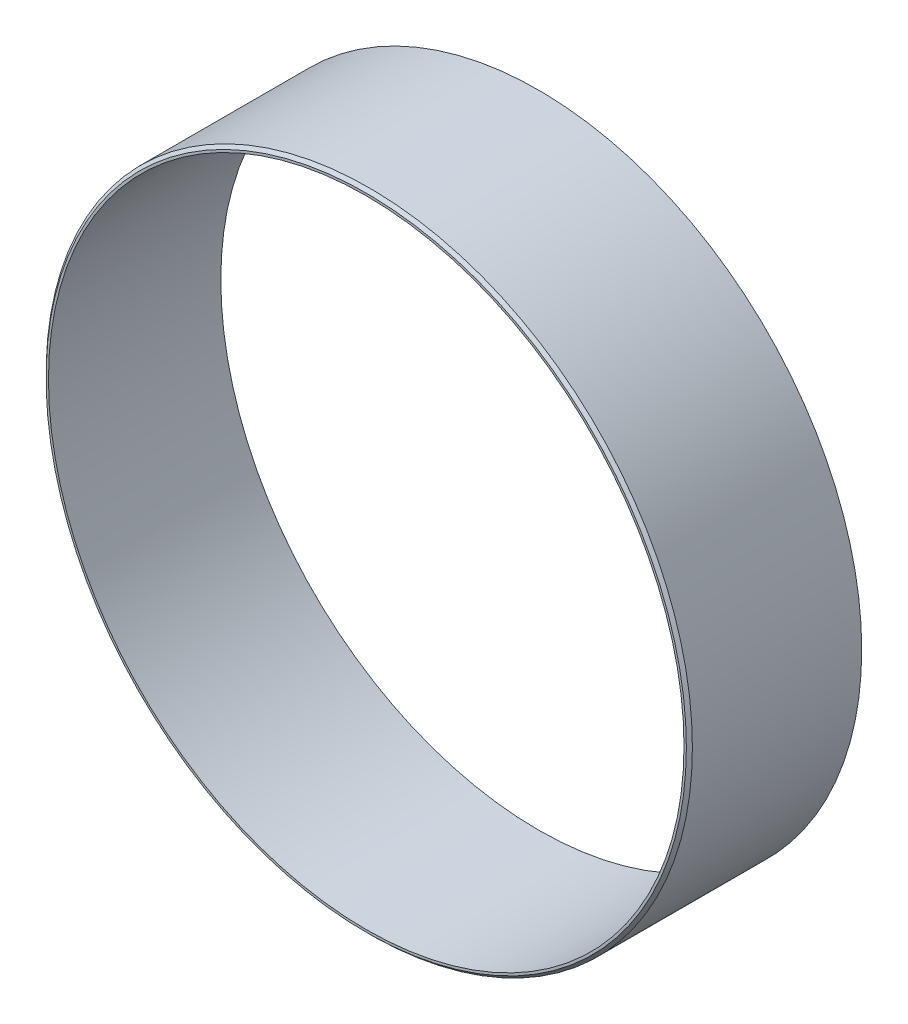
SolidWorks part; units mm, degrees
ref_plane "Piano frontale" through (0, 0, 0) normal (0, 0, 1) x (1, 0, 0)
ref_plane "Piano superiore" through (0, 0, 0) normal (0, 1, 0) x (1, 0, 0)
ref_plane "Piano destro" through (0, 0, 0) normal (1, 0, 0) x (0, 0, -1)
sketch "Schizzo1" plane through (0, 0, 0) normal (0, 0, 1) x (1, 0, 0)
  circle A0 centre (0, 0) radius 75
  circle A1 centre (0, 0) radius 73.75
  dimension "D1" = 147.5
  dimension "D2" = 150
extrude "Estrusione-Estrusione1" add sketch "Schizzo1" along normal blind 40
chamfer "Smusso1" distance 0.7 angle 45 1 edges at (75, 0, 40)
